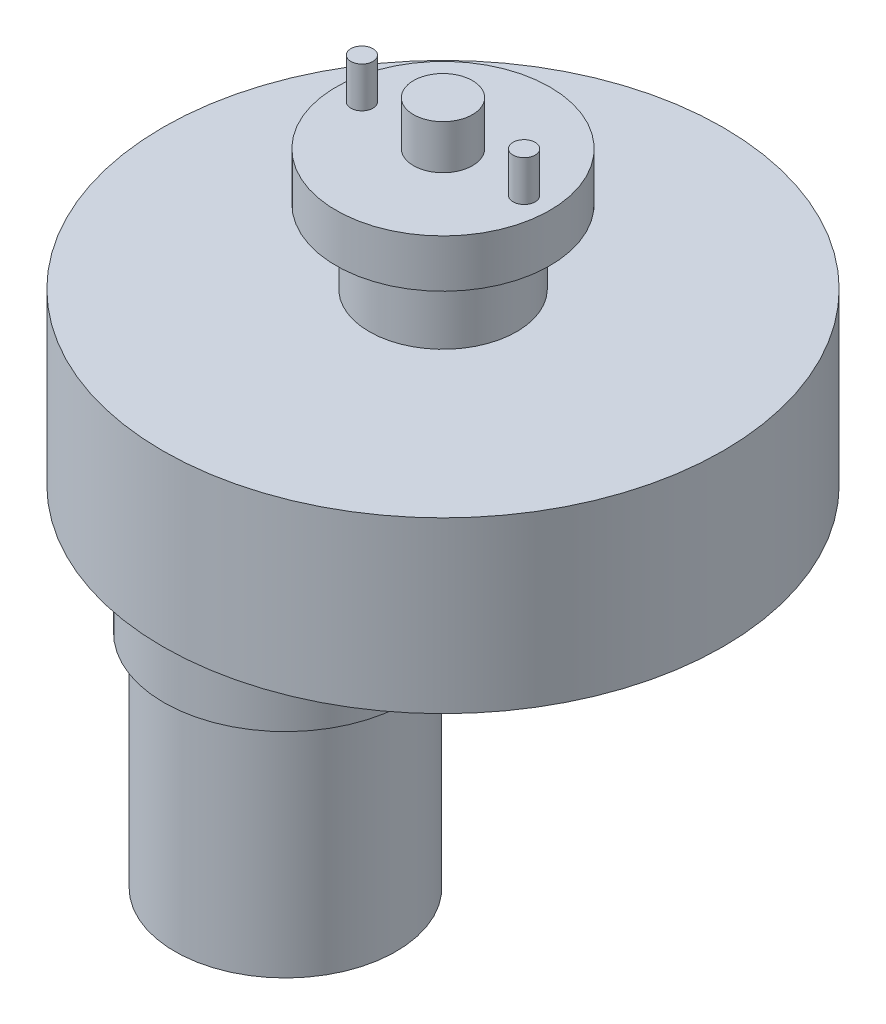
SolidWorks part; units mm, degrees
ref_plane "Спереди" through (0, 0, 0) normal (0, 0, 1) x (1, 0, 0)
ref_plane "Сверху" through (0, 0, 0) normal (0, 1, 0) x (1, 0, 0)
ref_plane "Справа" through (0, 0, 0) normal (1, 0, 0) x (0, 0, -1)
sketch "Эскиз1" plane through (0, 0, 0) normal (0, 1, 0) x (1, 0, 0)
  circle A0 centre (0, 0) radius 38
  dimension "D1" = 76
extrude "Вытянуть1" add sketch "Эскиз1" along normal blind 23
sketch "Эскиз2" plane through (0, 23, 0) normal (0, 1, 0) x (1, 0, 0)
  circle A0 centre (0, 0) radius 10
  dimension "D1" = 20
extrude "Вытянуть2" add sketch "Эскиз2" along normal blind 10
sketch "Эскиз3" plane through (0, 33, 0) normal (0, 1, 0) x (1, 0, 0)
  circle A0 centre (0, 0) radius 14.5
  dimension "D1" = 29
extrude "Вытянуть3" add sketch "Эскиз3" along normal blind 6.5
sketch "Эскиз4" plane through (0, 39.5, 0) normal (0, 1, 0) x (-1, 0, 0)
  circle A0 centre (0, 0) radius 4
extrude "Вытянуть4" add sketch "Эскиз4" along normal blind 6
sketch "Эскиз5" plane through (0, 39.5, 0) normal (0, 1, 0) x (-1, 0, 0)
  circle A0 centre (11, 0) radius 1.5
  circle A1 centre (-11, 0) radius 1.5
  circle A2 centre (0, 0) radius 14.5 construction
extrude "Вытянуть5" add sketch "Эскиз5" along normal blind 5.5
sketch "Эскиз6" plane through (0, 0, 0) normal (0, -1, 0) x (1, 0, 0)
  circle A0 centre (-21.3727, 0) radius 16.5
extrude "Вытянуть6" add sketch "Эскиз6" along normal blind 28
sketch "Эскиз7" plane through (0, -28, 0) normal (0, -1, 0) x (1, 0, 0)
  circle A0 centre (-21.3727, 0) radius 15
extrude "Вытянуть7" add sketch "Эскиз7" along normal blind 30
